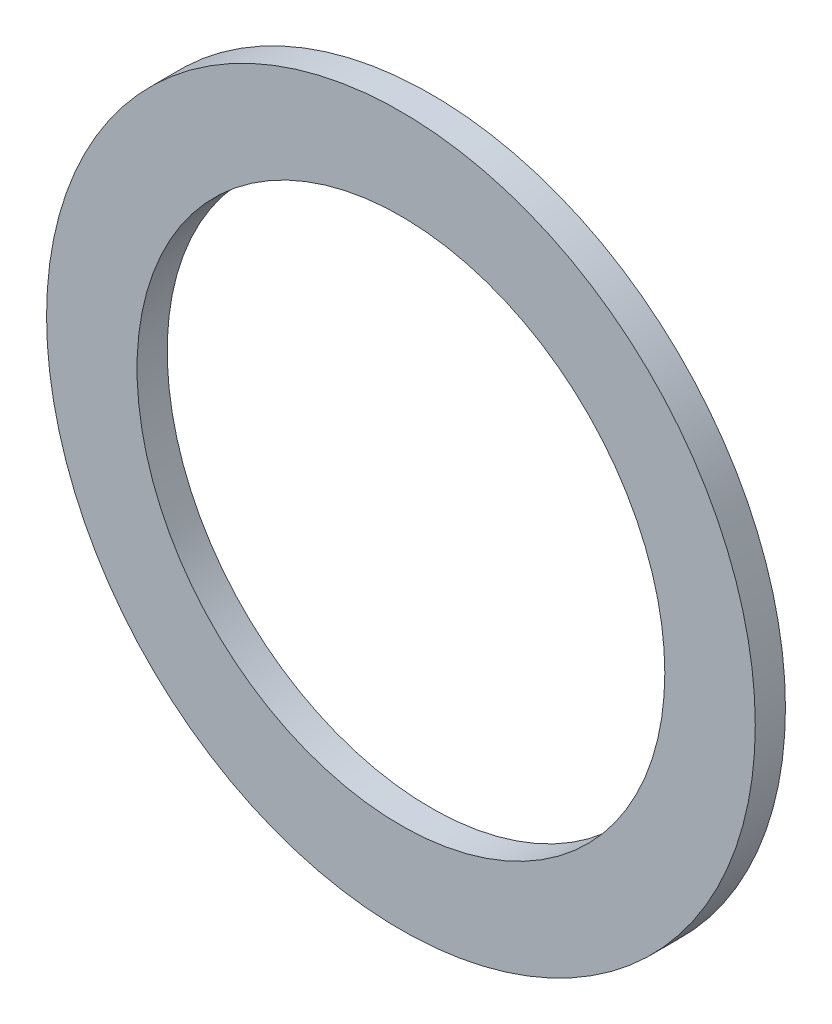
SolidWorks part; units mm, degrees
ref_plane "Front Plane" through (0, 0, 0) normal (0, 0, 1) x (1, 0, 0)
ref_plane "Top Plane" through (0, 0, 0) normal (0, 1, 0) x (1, 0, 0)
ref_plane "Right Plane" through (0, 0, 0) normal (1, 0, 0) x (0, 0, -1)
sketch "Sketch1" plane through (0, 0, 0) normal (0, 0, 1) x (1, 0, 0)
  circle A0 centre (0, 0) radius 23.5
  circle A1 centre (0, 0) radius 17.5
  dimension "D1" = 47
  dimension "D2" = 35
extrude "Boss-Extrude1" add sketch "Sketch1" along normal blind 2
